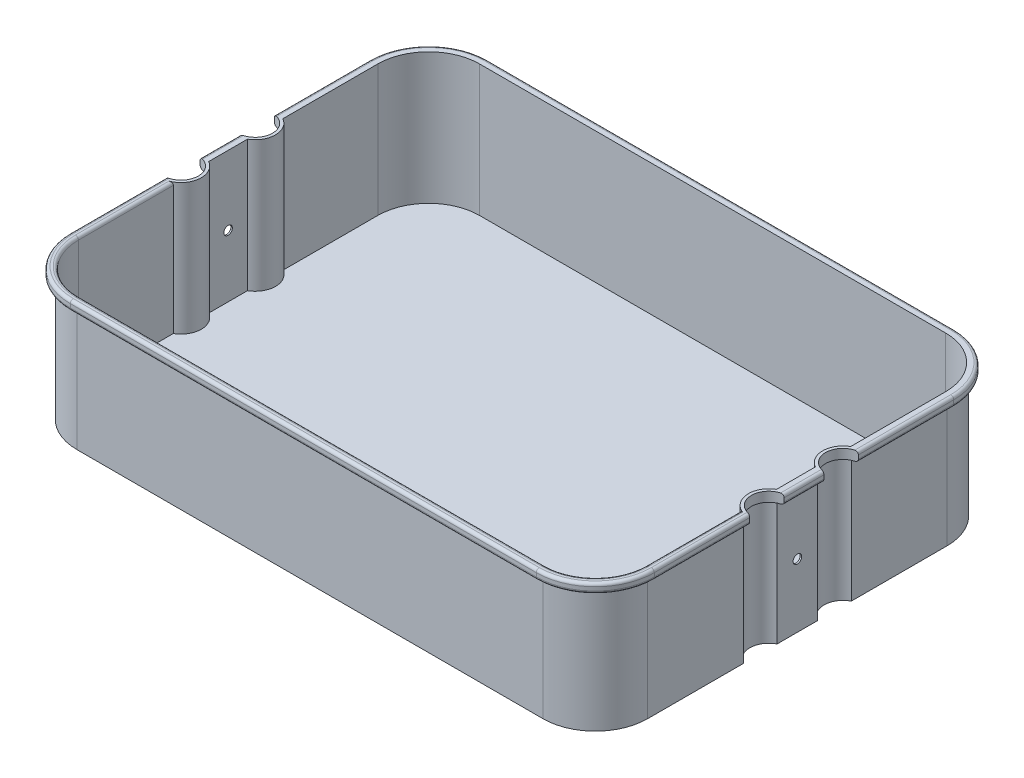
SolidWorks part; units mm, degrees
ref_plane "Front Plane" through (0, 0, 0) normal (0, 0, 1) x (1, 0, 0)
ref_plane "Top Plane" through (0, 0, 0) normal (0, 1, 0) x (1, 0, 0)
ref_plane "Right Plane" through (0, 0, 0) normal (1, 0, 0) x (0, 0, -1)
sketch "Sketch1" plane through (0, 0, 0) normal (0, 1, 0) x (1, 0, 0)
  line L0 (-192.5, -101.5) -> (-192.5, 101.5)
  line L1 (-158, -141.5) -> (158, -141.5) construction
  line L2 (-198, -101.5) -> (-198, 101.5) construction
  line L3 (-158, 141.5) -> (158, 141.5) construction
  line L4 (198, -101.5) -> (198, 101.5) construction
  line L5 (-198, -141.5) -> (198, 141.5) construction
  line L6 (-198, 141.5) -> (198, -141.5) construction
  line L7 (-158, 136) -> (158, 136)
  line L8 (192.5, -101.5) -> (192.5, 101.5)
  line L9 (-158, -136) -> (158, -136)
  line L10 (-49.5, 0) -> (49.5, 0) construction
  line L11 (0, -49.5) -> (0, 49.5) construction
  arc A0 (158, -141.5) -> (198, -101.5) centre (158, -101.5) ccw construction
  arc A1 (158, 141.5) -> (198, 101.5) centre (158, 101.5) cw construction
  arc A2 (-158, -141.5) -> (-198, -101.5) centre (-158, -101.5) cw construction
  arc A3 (-198, 101.5) -> (-158, 141.5) centre (-158, 101.5) cw construction
  arc A4 (-192.5, 101.5) -> (-158, 136) centre (-158, 101.5) cw
  arc A5 (158, 136) -> (192.5, 101.5) centre (158, 101.5) cw
  arc A6 (158, -136) -> (192.5, -101.5) centre (158, -101.5) ccw
  arc A7 (-158, -136) -> (-192.5, -101.5) centre (-158, -101.5) cw
  circle A9 centre (-199.25, -25.15) radius 11.15 construction
  circle A10 centre (-199.25, -25.15) radius 13.75 construction
  arc A11 (-192.5, -13.1709) -> (-192.5, -37.1291) centre (-199.25, -25.15) cw
  arc A12 (-192.5, 13.1709) -> (-192.5, 37.1291) centre (-199.25, 25.15) ccw
  arc A13 (192.5, -13.1709) -> (192.5, -37.1291) centre (199.25, -25.15) ccw
  arc A14 (192.5, 13.1709) -> (192.5, 37.1291) centre (199.25, 25.15) cw
  point P0 (0, 0)
  point P34 (-185.5, -25.15)
  dimension "D3" = 40
  dimension "D6" = 22.3
  dimension "D1" = 396
  dimension "D2" = 283
  dimension "D5" = 7
  dimension "D7" = 1.25
  dimension "D8" = 25.15
  dimension "D4" = 5.5
extrude "Boss-Extrude1" add sketch "Sketch1" against normal blind 89 contours L8 A14 A5 L7 A4 L0 A12 A11 A7 L9 A6 A13
shell "Shell1" thickness 1
sketch "Sketch2" plane through (0, 0, 0) normal (0, 1, 0) x (1, 0, 0)
  line L0 (-198, -101.5) -> (-198, 101.5) construction
  line L1 (-158, -141.5) -> (158, -141.5) construction
  line L2 (198, -101.5) -> (198, 101.5) construction
  line L3 (-158, 141.5) -> (158, 141.5) construction
  line L4 (-198, -101.5) -> (-198, 101.5)
  line L5 (-158, -141.5) -> (158, -141.5)
  line L6 (198, -101.5) -> (198, 101.5)
  line L7 (-158, 141.5) -> (158, 141.5)
  line L8 (-49.5, 0) -> (49.5, 0) construction
  line L9 (0, -49.5) -> (0, 49.5) construction
  arc A1 (-198, -101.5) -> (-158, -141.5) centre (-158, -101.5) ccw construction
  arc A2 (158, -141.5) -> (198, -101.5) centre (158, -101.5) ccw construction
  arc A3 (198, 101.5) -> (158, 141.5) centre (158, 101.5) ccw construction
  arc A4 (-158, 141.5) -> (-198, 101.5) centre (-158, 101.5) ccw construction
  arc A5 (-198, -101.5) -> (-158, -141.5) centre (-158, -101.5) ccw
  arc A6 (158, -141.5) -> (198, -101.5) centre (158, -101.5) ccw
  arc A7 (198, 101.5) -> (158, 141.5) centre (158, 101.5) ccw
  arc A8 (-158, 141.5) -> (-198, 101.5) centre (-158, 101.5) ccw
  circle A9 centre (-199.25, -25.15) radius 11.75
  arc A10 (-193.5, -36.5298) -> (-193.5, -13.7702) centre (-199.25, -25.15) ccw construction
  circle A11 centre (-199.25, 25.15) radius 11.75
  circle A12 centre (199.25, -25.15) radius 11.75
  circle A13 centre (199.25, 25.15) radius 11.75
  line M25 (193.5, -13.7702) -> (193.5, 13.7702)
  arc M26 (193.5, 13.7702) -> (193.5, 36.5298) centre (199.25, 25.15) cw
  line M27 (193.5, 36.5298) -> (193.5, 101.5)
  arc M28 (193.5, 101.5) -> (158, 137) centre (158, 101.5) ccw
  line M29 (158, 137) -> (-158, 137)
  arc M30 (-158, 137) -> (-193.5, 101.5) centre (-158, 101.5) ccw
  line M31 (-193.5, 101.5) -> (-193.5, 36.5298)
  arc M32 (-193.5, 36.5298) -> (-193.5, 13.7702) centre (-199.25, 25.15) cw
  line M33 (-193.5, 13.7702) -> (-193.5, -13.7702)
  arc M34 (-193.5, -13.7702) -> (-193.5, -36.5298) centre (-199.25, -25.15) cw
  line M35 (-193.5, -36.5298) -> (-193.5, -101.5)
  arc M36 (-193.5, -101.5) -> (-158, -137) centre (-158, -101.5) ccw
  line M37 (-158, -137) -> (158, -137)
  arc M38 (158, -137) -> (193.5, -101.5) centre (158, -101.5) ccw
  line M39 (193.5, -101.5) -> (193.5, -36.5298)
  arc M40 (193.5, -36.5298) -> (193.5, -13.7702) centre (199.25, -25.15) cw
  dimension "D1" = 1
extrude "Boss-Extrude2" add sketch "Sketch2" against normal blind 6.5 contours A13 L6 A7 L7 A8 L4 A11 A9 A5 L5 A6 A12 M25 M40 M39 M38 M37 M36 M35 M34 M33 M32 M31 M30 M29 M28 M27 M26
fillet "Fillet1" radius 2 29 edges at (-192.5, 0, 69.3146) (-182.3952, 0, 125.8952) (0, 0, 136) (192.5, 0, 69.3146) (-198, -6.5, 69.1667) (-186.2843, -6.5, 129.7843) (0, -6.5, 141.5) (198, -6.5, 69.1667) (-198, 0, 69.1667) (-186.2843, 0, 129.7843) (0, 0, 141.5) (198, 0, 69.1667) (182.3952, 0, 125.8952) (186.2843, -6.5, 129.7843) (186.2843, 0, 129.7843) (-198, -6.5, -69.1667) (-186.2843, -6.5, -129.7843) (0, -6.5, -141.5) (186.2843, -6.5, -129.7843) (-198, 0, -69.1667) (-186.2843, 0, -129.7843) (0, 0, -141.5) (186.2843, 0, -129.7843) (-198, -6.5, 0) (-198, 0, 0) (198, -6.5, -69.1667) (198, 0, -69.1667) (198, -6.5, 0) (198, 0, 0)
sketch "Sketch3" plane through (-193.5, 0, 0) normal (-1, 0, 0) x (0, 0, 1)
  line L0 (0, -90) -> (0, -47) construction
  line L1 (13.7702, -90) -> (-13.7702, -90) construction
  circle A0 centre (0, -47) radius 2.9
  dimension "D1" = 5.8
  dimension "D2" = 43
extrude "Cut-Extrude1" cut sketch "Sketch3" against normal through all
equation "\"Width\" = 396"
equation "\"D1@Sketch1\"=\"Width\""
equation "\"Height\" = 283"
equation "\"D2@Sketch1\"=\"Height\""
